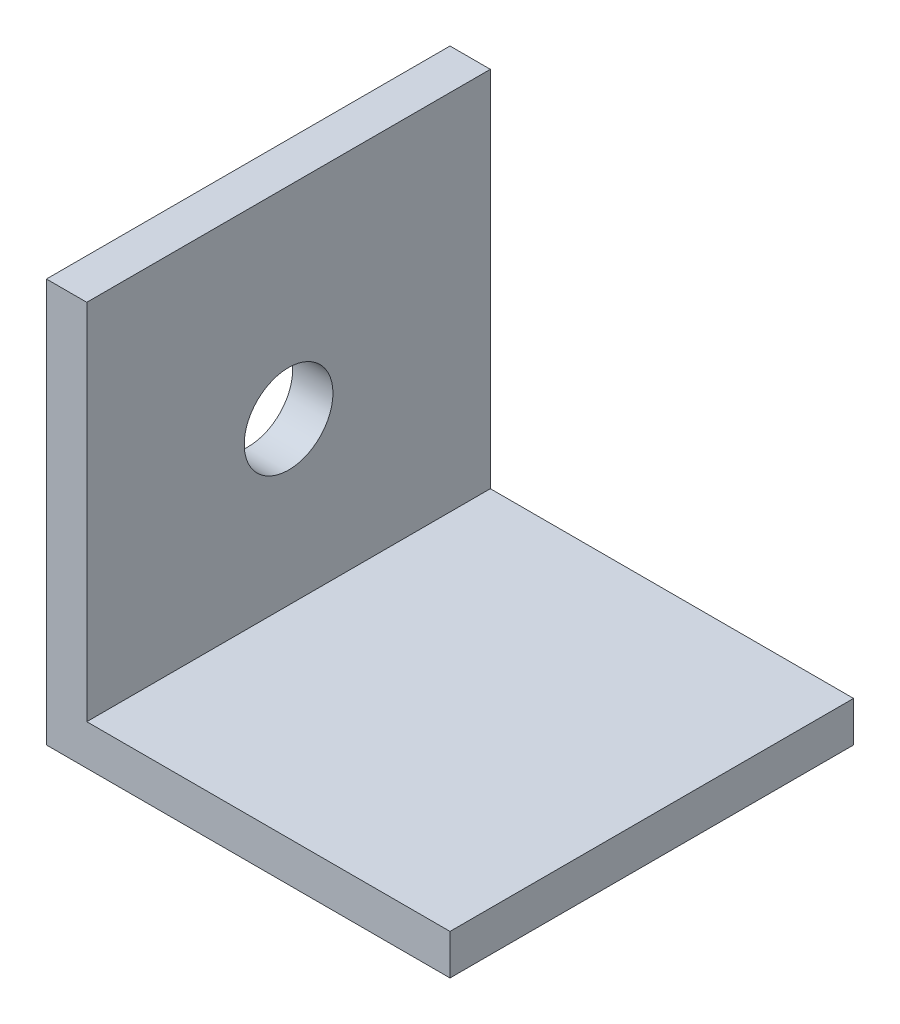
SolidWorks part; units mm, degrees
ref_plane "Front Plane" through (0, 0, 0) normal (0, 0, 1) x (1, 0, 0)
ref_plane "Top Plane" through (0, 0, 0) normal (0, 1, 0) x (1, 0, 0)
ref_plane "Right Plane" through (0, 0, 0) normal (1, 0, 0) x (0, 0, -1)
sketch "Sketch1" plane through (0, 0, 0) normal (0, 0, 1) x (1, 0, 0)
  line L0 (0, 0) -> (0, 50)
  line L1 (0, 0) -> (50, 0)
  dimension "D1" = 50
  dimension "D2" = 50
extrude "Extrude-Thin1" add sketch "Sketch1" along normal mid plane 50 thin
sketch "Sketch2" plane through (0, 0, 0) normal (1, 0, 0) x (0, 1, 0)
  line L0 (50, 25) -> (0, 25) construction
  line L1 (50, 25) -> (50, -25) construction
  circle A0 centre (25, 0) radius 5.5
  point P4 (25, 25)
  point P7 (50, 0)
  dimension "D1" = 11
extrude "Cut-Extrude1" cut sketch "Sketch2" along normal blind 5
